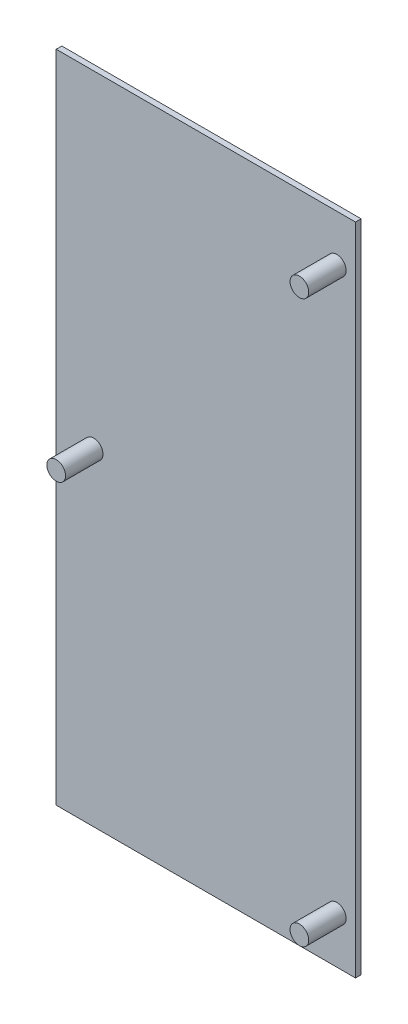
SolidWorks part; units mm, degrees
ref_plane "Front Plane" through (0, 0, 0) normal (0, 0, 1) x (1, 0, 0)
ref_plane "Top Plane" through (0, 0, 0) normal (0, 1, 0) x (1, 0, 0)
ref_plane "Right Plane" through (0, 0, 0) normal (1, 0, 0) x (0, 0, -1)
sketch "Sketch1" plane through (0, 0, 0) normal (0, 0, 1) x (1, 0, 0)
  line L1 (-80, 175) -> (80, 175)
  line L2 (-80, 175) -> (-80, -175)
  line L3 (-80, -175) -> (80, -175)
  line L4 (80, 175) -> (80, -175)
  line L5 (-80, 175) -> (80, -175) construction
  line L6 (-80, -175) -> (80, 175) construction
  point P0 (0, 0)
  dimension "D1" = 350
  dimension "D2" = 160
extrude "Boss-Extrude1" add sketch "Sketch1" along normal blind 3
sketch "Sketch2" plane through (0, 0, 3) normal (0, 0, 1) x (1, 0, 0)
  line L0 (70, 175) -> (70, -175) construction
  line L1 (80, 175) -> (-80, 175) construction
  line L2 (-80, -175) -> (80, -175) construction
  circle A0 centre (70, 150) radius 5
  dimension "D2" = 10
  dimension "D1" = 10
  dimension "D3" = 150
extrude "Boss-Extrude2" add sketch "Sketch2" along normal blind 20
mirror "Mirror1" about plane through (0, 0, 0) normal (0, 1, 0) of "Boss-Extrude2"
sketch "Sketch3" plane through (0, 0, 3) normal (0, 0, 1) x (1, 0, 0)
  line L0 (80, 0) -> (-60, 0) construction
  line L1 (80, -175) -> (80, 175) construction
  circle A0 centre (-60, 0) radius 5
  dimension "D2" = 10
  dimension "D1" = 140
extrude "Boss-Extrude3" add sketch "Sketch3" along normal blind 20
